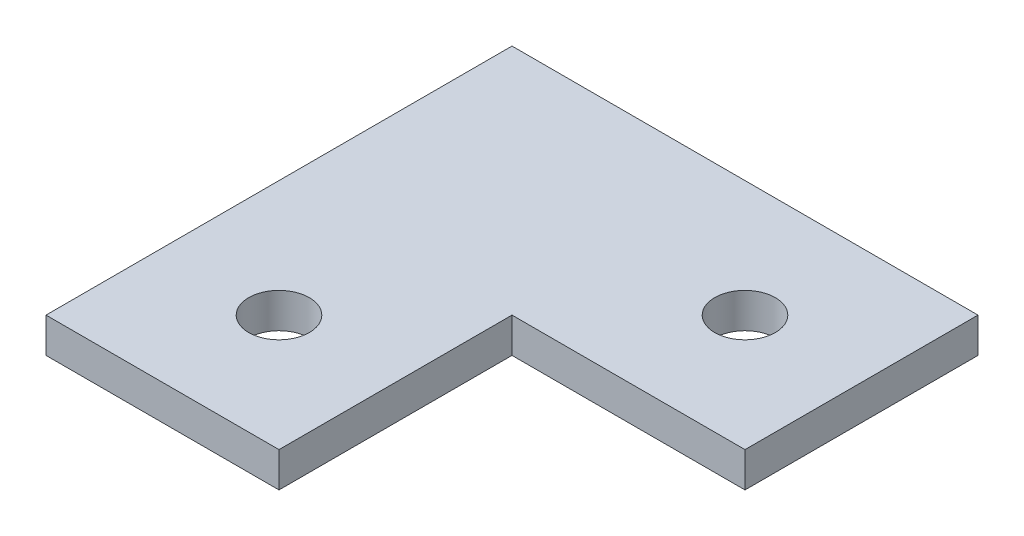
SolidWorks part; units mm, degrees
ref_plane "Front Plane" through (0, 0, 0) normal (0, 0, 1) x (1, 0, 0)
ref_plane "Top Plane" through (0, 0, 0) normal (0, 1, 0) x (1, 0, 0)
ref_plane "Right Plane" through (0, 0, 0) normal (1, 0, 0) x (0, 0, -1)
sketch "Sketch1" plane through (0, 0, 0) normal (0, 1, 0) x (1, 0, 0)
  line L0 (-20, 20) -> (-20, -20)
  line L1 (-20, -20) -> (0, -20)
  line L2 (0, -20) -> (0, 0)
  line L3 (0, 0) -> (20, 0)
  line L4 (20, 0) -> (20, 20)
  line L5 (20, 20) -> (-20, 20)
  circle A0 centre (-10, -10) radius 2.6
  circle A1 centre (10, 10) radius 2.6
  dimension "D5" = 5.2
  dimension "D6" = 5.2
  dimension "D7" = 10
  dimension "D8" = 10
  dimension "D9" = 10
  dimension "D10" = 10
  dimension "D1" = 40
  dimension "D2" = 40
  dimension "D3" = 20
  dimension "D4" = 20
  dimension "D11" = 0
extrude "Boss-Extrude1" add sketch "Sketch1" along normal blind 3
